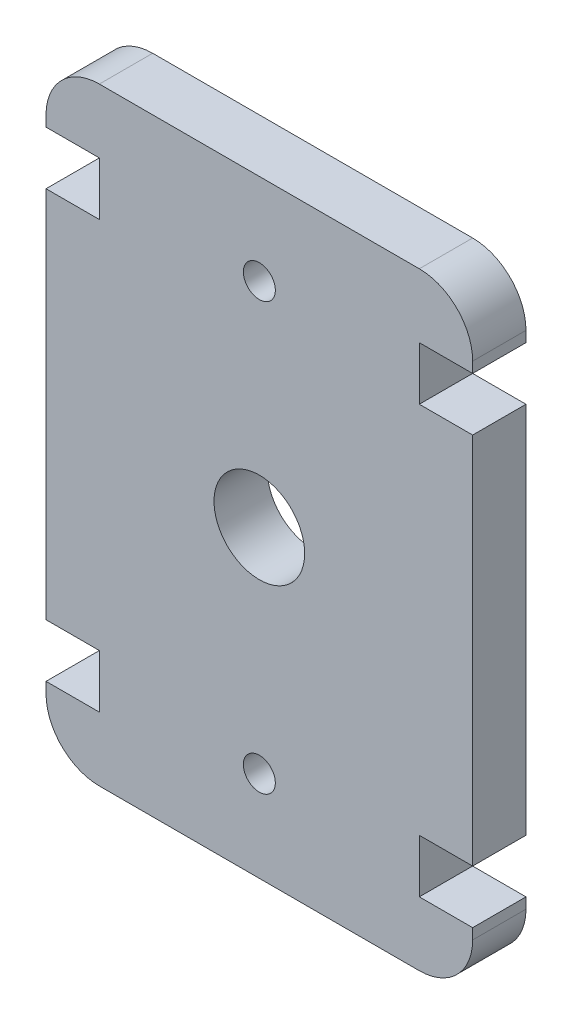
SolidWorks part; units mm, degrees
ref_plane "Plan de face" through (0, 0, 0) normal (0, 0, 1) x (1, 0, 0)
ref_plane "Plan de dessus" through (0, 0, 0) normal (0, 1, 0) x (1, 0, 0)
ref_plane "Plan de droite" through (0, 0, 0) normal (1, 0, 0) x (0, 0, -1)
sketch "Esquisse1" plane through (0, 0, 0) normal (0, 0, 1) x (1, 0, 0)
  line L0 (-20, 0) -> (20, 0)
  line L1 (20, 0) -> (20, 6)
  line L2 (20, 6) -> (15, 6)
  line L3 (15, 6) -> (15, 11)
  line L4 (15, 11) -> (20, 11)
  line L5 (20, 11) -> (20, 46)
  line L6 (20, 46) -> (15, 46)
  line L7 (15, 46) -> (15, 51)
  line L8 (15, 51) -> (20, 51)
  line L9 (20, 51) -> (20, 57)
  line L10 (20, 57) -> (-20, 57)
  line L11 (-20, 57) -> (-20, 51)
  line L12 (-20, 51) -> (-15, 51)
  line L13 (-15, 51) -> (-15, 46)
  line L14 (-15, 46) -> (-20, 46)
  line L15 (-20, 46) -> (-20, 11)
  line L16 (-20, 11) -> (-15, 11)
  line L17 (-15, 11) -> (-15, 6)
  line L18 (-15, 6) -> (-20, 6)
  line L19 (-20, 6) -> (-20, 0)
  line L20 (0, 0) -> (0, 57) construction
  line L21 (-15, 8.5) -> (15, 8.5) construction
  line L22 (15, 48.5) -> (-15, 48.5) construction
  line L23 (-20, 28.5) -> (20, 28.5) construction
  circle A0 centre (0, 48.5) radius 1.5
  circle A1 centre (0, 8.5) radius 1.5
  circle A2 centre (0, 28.5) radius 4.25
  circle A3 centre (-20, 28.5) radius 1.6 construction
  circle A4 centre (20, 28.5) radius 1.6 construction
  dimension "D6" = 3
  dimension "D7" = 3
  dimension "D8" = 8.5
  dimension "D10" = 3.2
  dimension "D1" = 5
  dimension "D2" = 30
  dimension "D3" = 40
  dimension "D4" = 6
  dimension "D5" = 40
  dimension "D9" = 40
  dimension "D11" = 20
extrude "Boss.-Extru.1" add sketch "Esquisse1" along normal blind 5
fillet "Congé1" radius 5 4 edges at (20, 57, 2.5) (20, 0, 2.5) (-20, 0, 2.5) (-20, 57, 2.5)
